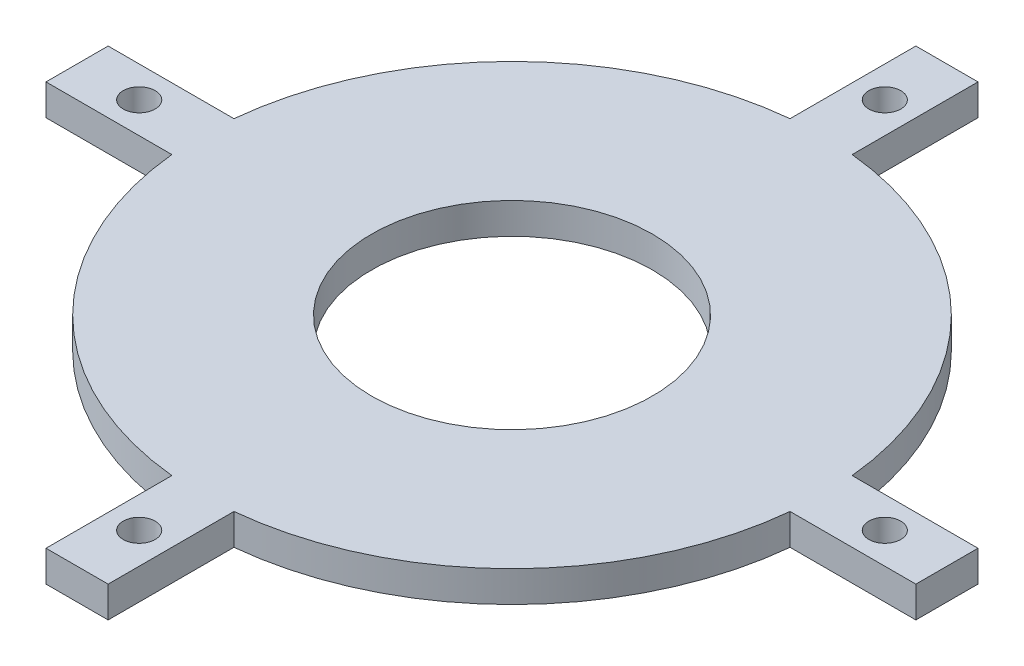
SolidWorks part; units mm, degrees
ref_plane "Front Plane" through (0, 0, 0) normal (0, 0, 1) x (1, 0, 0)
ref_plane "Top Plane" through (0, 0, 0) normal (0, 1, 0) x (1, 0, 0)
ref_plane "Right Plane" through (0, 0, 0) normal (1, 0, 0) x (0, 0, -1)
sketch "Sketch1" plane through (0, 0, 0) normal (0, 1, 0) x (1, 0, 0)
  circle A0 centre (0, 0) radius 46.99
  dimension "D1" = 93.98
extrude "Boss-Extrude1" add sketch "Sketch1" along normal blind 3.175
sketch "Sketch2" plane through (0, 3.175, 0) normal (0, 1, 0) x (1, 0, 0)
  circle A0 centre (0, 0) radius 14.351
  dimension "D1" = 28.702
extrude "Cut-Extrude1" cut sketch "Sketch2" against normal blind 3.175
sketch "Sketch5" plane through (0, 3.175, 0) normal (0, 1, 0) x (1, 0, 0)
  line L1 (3.175, 44.45) -> (-3.175, 44.45)
  line L2 (3.175, 44.45) -> (3.175, -44.45)
  line L3 (3.175, -44.45) -> (-3.175, -44.45)
  line L4 (-3.175, 44.45) -> (-3.175, -44.45)
  line L5 (3.175, 44.45) -> (-3.175, -44.45) construction
  line L6 (3.175, -44.45) -> (-3.175, 44.45) construction
  line L7 (-44.45, 3.175) -> (44.45, 3.175)
  line L8 (-44.45, 3.175) -> (-44.45, -3.175)
  line L9 (-44.45, -3.175) -> (44.45, -3.175)
  line L10 (44.45, 3.175) -> (44.45, -3.175)
  line L11 (-44.45, 3.175) -> (44.45, -3.175) construction
  line L12 (-44.45, -3.175) -> (44.45, 3.175) construction
  circle A0 centre (0, 0) radius 31.75
  circle A1 centre (0, 0) radius 44.45
  point P0 (0, 0)
  point P6 (0, 0)
  circle M2 centre (0, 0) radius 46.99
  dimension "D5" = 88.9
  dimension "D6" = 63.5
  dimension "D1" = 6.35
  dimension "D2" = 88.9
  dimension "D3" = 88.9
  dimension "D4" = 6.35
extrude "Cut-Extrude2" cut sketch "Sketch5" against normal blind 5.08 contours L4 A1 L7 A0 | L7 A1 L2 A0 | L2 A1 L9 A0 | L9 A1 L4 A0 | A1 L2 L3 L4 L9 L8 L7 L1 L10 M2
hole_wizard "#4 Clearance Hole1" positions "Sketch7" profile "Sketch6" hole size "#4" standard "ANSI Inch"
sketch "Sketch7" plane through (0, 3.175, 0) normal (0, 1, 0) x (1, 0, 0)
  point P0 (0, 38.1)
  dimension "D1" = 38.1
sketch "Sketch6" plane through (0, 3.175, -38.1) normal (1, 0, 0) x (0, 0, 1)
  line L0 (0, 0) -> (0, 11.1406)
  line L1 (0, 11.1406) -> (1.6319, 10.16)
  line L2 (1.6319, 10.16) -> (1.6319, 0)
  line L5 (1.6319, 0) -> (0, 0)
  line L10 (0, 11.1406) -> (-1.6319, 10.16) construction
  line L11 (0, -6.35) -> (0, 107.95) construction
  dimension "Hole Dia." = 3.2639
  dimension "Hole Depth" = 10.16
  dimension "Drill Angle" = 118
pattern_circular "CirPattern1" count 4 every 90 about axis through (0, 0, 0) along (0, 1, 0) of "#4 Clearance Hole1"
